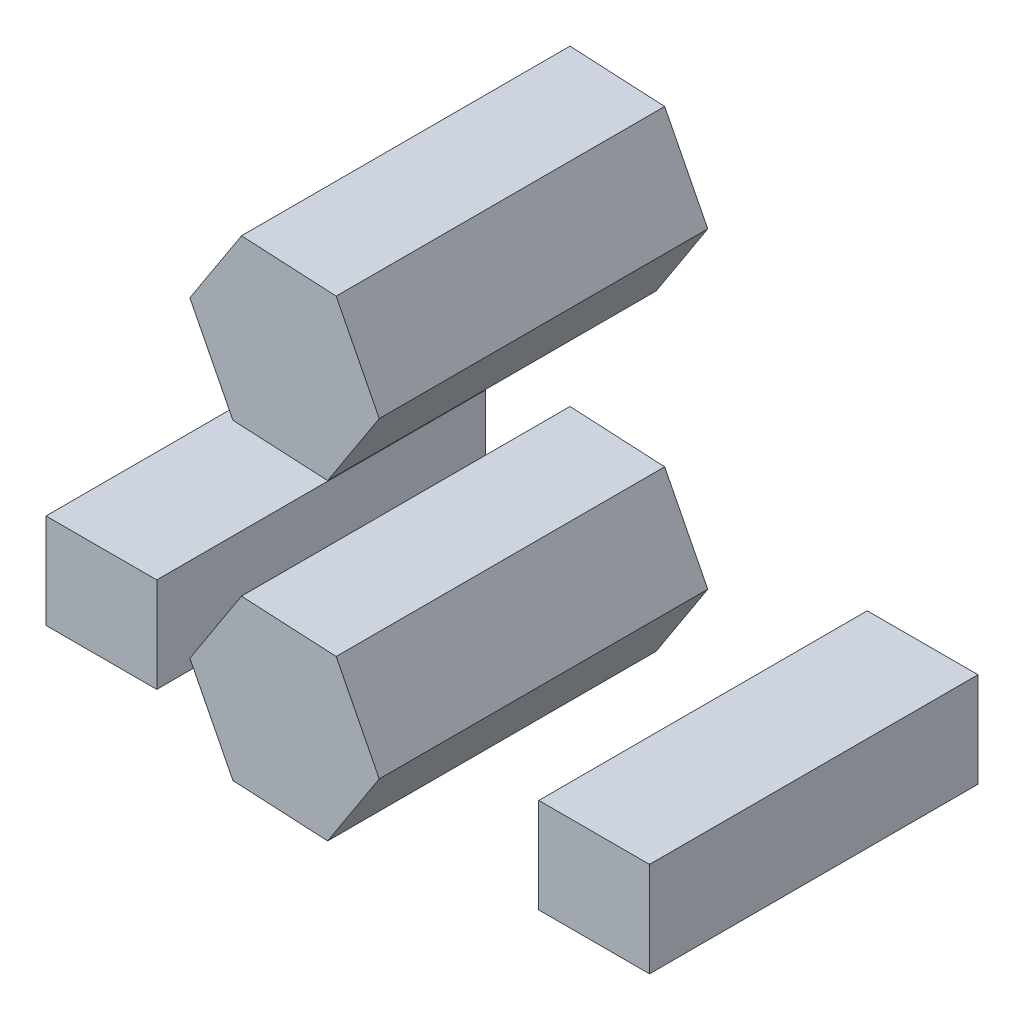
SolidWorks part; units mm, degrees
ref_plane "Front Plane" through (0, 0, 0) normal (0, 0, 1) x (1, 0, 0)
ref_plane "Top Plane" through (0, 0, 0) normal (0, 1, 0) x (1, 0, 0)
ref_plane "Right Plane" through (0, 0, 0) normal (1, 0, 0) x (0, 0, -1)
sketch "Sketch1" plane through (0, 0, 0) normal (0, 0, 1) x (1, 0, 0)
  line L1 (57.6569, -3.003) -> (31.4291, 48.4308)
  line L2 (31.4291, 48.4308) -> (-26.2278, 51.4338)
  line L3 (-26.2278, 51.4338) -> (-57.6569, 3.003)
  line L4 (-57.6569, 3.003) -> (-31.4291, -48.4308)
  line L5 (-31.4291, -48.4308) -> (26.2278, -51.4338)
  line L6 (26.2278, -51.4338) -> (57.6569, -3.003)
  circle A0 centre (0, 0) radius 50 construction
extrude "Boss-Extrude1" add sketch "Sketch1" along normal blind 200
sketch "Sketch2" plane through (0, 0, 0) normal (0, 0, 1) x (1, 0, 0)
  line L1 (-145.2492, 34.1901) -> (-77.8121, 34.1901)
  line L2 (-145.2492, 34.1901) -> (-145.2492, -23.5499)
  line L3 (-145.2492, -23.5499) -> (-77.8121, -23.5499)
  line L4 (-77.8121, 34.1901) -> (-77.8121, -23.5499)
  line L5 (-145.2492, 34.1901) -> (-77.8121, -23.5499) construction
  line L6 (-145.2492, -23.5499) -> (-77.8121, 34.1901) construction
  point P0 (-111.5306, 5.3201)
  dimension "D1" = 57.74
extrude "Boss-Extrude2" add sketch "Sketch2" along normal blind 200 separate body
move or copy body "Body-Move/Copy1" bodies to move or copy 102 copy yes number of copies 1 translate (300, 0, 0) parameters "D1"=300, "D2"=0, "D3"=0
move or copy body "Body-Move/Copy2" bodies to move or copy 101 copy yes number of copies 1 translate (0, 190, 0) parameters "D1"=0, "D2"=190, "D3"=0
